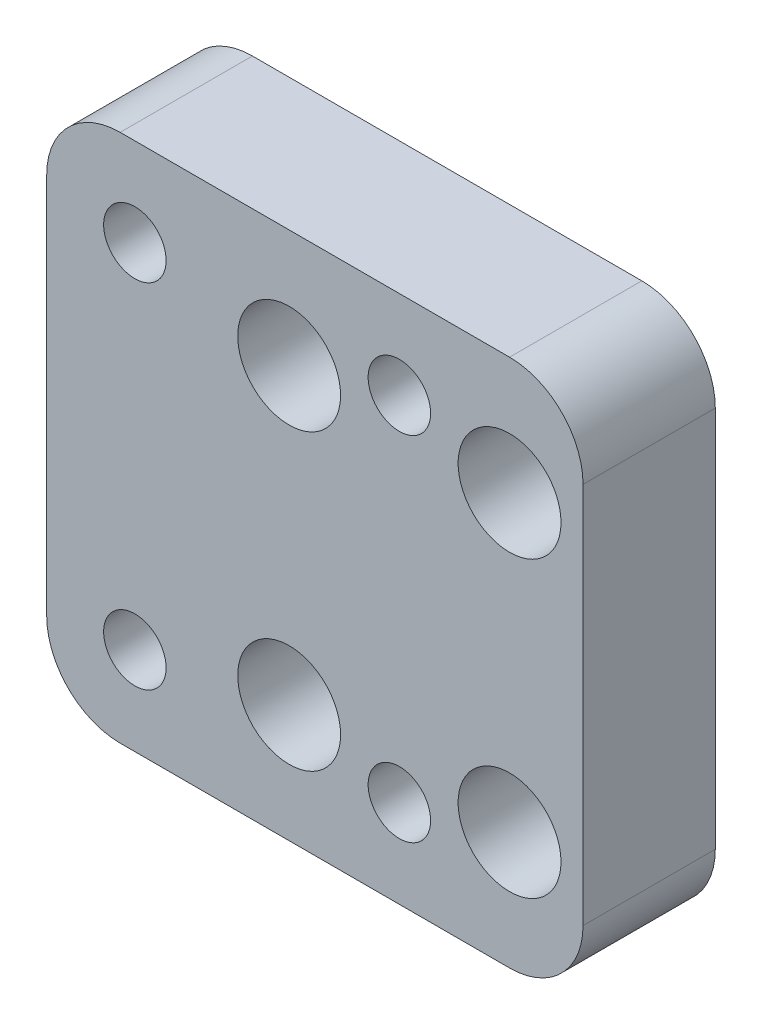
SolidWorks part; units mm, degrees
ref_plane "Front Plane" through (0, 0, 0) normal (0, 0, 1) x (1, 0, 0)
ref_plane "Top Plane" through (0, 0, 0) normal (0, 1, 0) x (1, 0, 0)
ref_plane "Right Plane" through (0, 0, 0) normal (1, 0, 0) x (0, 0, -1)
sketch "Sketch1" plane through (0, 0, 0) normal (0, 0, 1) x (1, 0, 0)
  line L0 (-28.7683, 14.4615) -> (-28.7683, 0) construction
  line L1 (0, 0) -> (15, 0) construction
  line L2 (0, 0) -> (0, 20) construction
  line L3 (0, 20) -> (15, 20) construction
  line L4 (15, 0) -> (15, 20) construction
  line L5 (-28.7683, 0) -> (-25.9188, 0) construction
  line L6 (-25.9188, 0) -> (-25.9188, 5.2985) construction
  line L7 (-25.9188, 5.2985) -> (-20.2199, 5.2985) construction
  line L8 (-20.2199, 5.2985) -> (-20.2199, 7.7568) construction
  line L9 (-20.2199, 7.7568) -> (-25.9188, 7.7568) construction
  line L10 (-25.9188, 7.7568) -> (-25.9188, 12.1707) construction
  line L11 (-25.9188, 12.1707) -> (-20.2199, 12.1707) construction
  line L12 (-20.2199, 12.1707) -> (-20.2199, 14.4615) construction
  line L13 (-20.2199, 14.4615) -> (-28.7683, 14.4615) construction
  line L15 (-10.5, 22) -> (7.5, 22) construction
  line L16 (-10.5, 22) -> (-10.5, -2) construction
  line L17 (-10.5, -2) -> (7.5, -2) construction
  line L18 (7.5, 22) -> (7.5, -2) construction
  line L19 (-16.5, 28) -> (20, 28)
  line L20 (-16.5, 28) -> (-16.5, -8)
  line L21 (-16.5, -8) -> (20, -8)
  line L22 (20, 28) -> (20, -8)
  circle A0 centre (0, 20) radius 1.625
  circle A1 centre (15, 20) radius 1.625
  circle A2 centre (15, 0) radius 1.625
  circle A3 centre (0, 0) radius 1.625
  circle A4 centre (-10.5, 22) radius 2.125
  circle A5 centre (7.5, 22) radius 2.125
  circle A6 centre (7.5, -2) radius 2.125
  circle A7 centre (-10.5, -2) radius 2.125
  point P27 (0, 10)
  point P28 (-10.5, 10)
  point P33 (-16.5, 10)
  dimension "D3" = 3.25
  dimension "D6" = 4.25
  dimension "D1" = 20
  dimension "D2" = 15
  dimension "D4" = 24
  dimension "D5" = 18
  dimension "D7" = 7.5
  dimension "D8" = 6
  dimension "D9" = 5
  dimension "D10" = 6
extrude "Boss-Extrude1" add sketch "Sketch1" along normal blind 9
sketch "Sketch2" plane through (0, 0, 9) normal (0, 0, 1) x (1, 0, 0)
  circle A0 centre (0, 20) radius 3.5
  circle A1 centre (0, 0) radius 3.5
  circle A2 centre (15, 0) radius 3.5
  circle A3 centre (15, 20) radius 3.5
  circle A4 centre (0, 20) radius 1.625 construction
  circle A5 centre (15, 20) radius 1.625 construction
  circle A6 centre (15, 0) radius 1.625 construction
  circle A7 centre (0, 0) radius 1.625 construction
  dimension "D1" = 7
extrude "Cut-Extrude1" cut sketch "Sketch2" against normal offset from surface (5 mm away) 4 up to face at (1.75, 10, 0)
sketch "Sketch3" plane through (0, 0, 0) normal (0, 0, -1) x (-1, 0, 0)
  line L1 (-5.3349, 18.25) -> (-3.1699, 22)
  line L2 (-3.1699, 22) -> (-5.3349, 25.75)
  line L3 (-5.3349, 25.75) -> (-9.6651, 25.75)
  line L4 (-9.6651, 25.75) -> (-11.8301, 22)
  line L5 (-11.8301, 22) -> (-9.6651, 18.25)
  line L6 (-9.6651, 18.25) -> (-5.3349, 18.25)
  line L7 (12.6651, 18.25) -> (14.8301, 22)
  line L8 (14.8301, 22) -> (12.6651, 25.75)
  line L9 (12.6651, 25.75) -> (8.3349, 25.75)
  line L10 (8.3349, 25.75) -> (6.1699, 22)
  line L11 (6.1699, 22) -> (8.3349, 18.25)
  line L12 (8.3349, 18.25) -> (12.6651, 18.25)
  line L13 (12.6651, -5.75) -> (14.8301, -2)
  line L14 (14.8301, -2) -> (12.6651, 1.75)
  line L15 (12.6651, 1.75) -> (8.3349, 1.75)
  line L16 (8.3349, 1.75) -> (6.1699, -2)
  line L17 (6.1699, -2) -> (8.3349, -5.75)
  line L18 (8.3349, -5.75) -> (12.6651, -5.75)
  line L19 (-9.6651, -5.75) -> (-5.3349, -5.75)
  line L20 (-5.3349, -5.75) -> (-3.1699, -2)
  line L21 (-3.1699, -2) -> (-5.3349, 1.75)
  line L22 (-5.3349, 1.75) -> (-9.6651, 1.75)
  line L23 (-9.6651, 1.75) -> (-11.8301, -2)
  line L24 (-11.8301, -2) -> (-9.6651, -5.75)
  circle A0 centre (-7.5, 22) radius 3.75 construction
  circle A1 centre (10.5, 22) radius 3.75 construction
  circle A2 centre (10.5, -2) radius 3.75 construction
  circle A3 centre (-7.5, -2) radius 3.75 construction
  circle A4 centre (-7.5, -2) radius 2.125 construction
  circle A6 centre (-7.5, 22) radius 2.125 construction
  dimension "D1" = 7.5
extrude "Cut-Extrude2" cut sketch "Sketch3" against normal offset from surface (5 mm away) 4 up to face at (18.5, 20, 9)
fillet "Fillet2" radius 5 4 edges at (-16.5, 28, 4.5) (-16.5, -8, 4.5) (20, 28, 4.5) (20, -8, 4.5)
